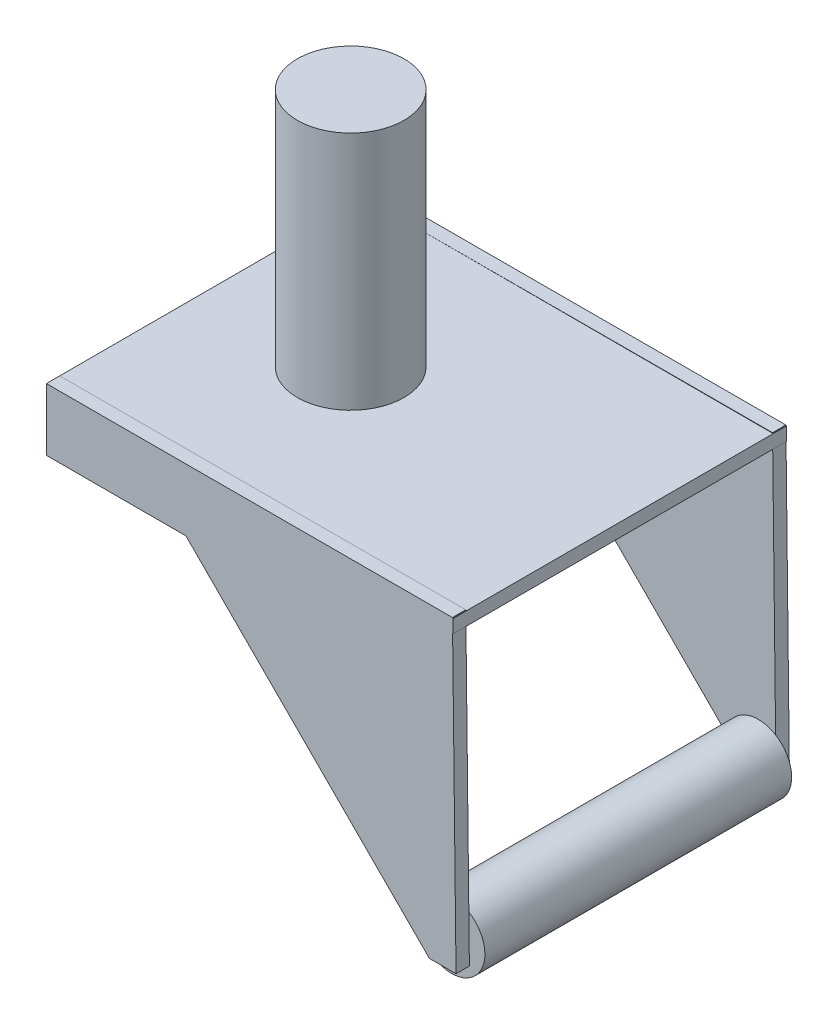
SolidWorks part; units mm, degrees
ref_plane "Plan de face" through (0, 0, 0) normal (0, 0, 1) x (1, 0, 0)
ref_plane "Plan de dessus" through (0, 0, 0) normal (0, 1, 0) x (1, 0, 0)
ref_plane "Plan de droite" through (0, 0, 0) normal (1, 0, 0) x (0, 0, -1)
sketch "Esquisse1" plane through (0, 0, 0) normal (0, 1, 0) x (1, 0, 0)
  line L1 (-15.25, 12.5) -> (15.25, 12.5)
  line L2 (-15.25, 12.5) -> (-15.25, -12.5)
  line L3 (-15.25, -12.5) -> (15.25, -12.5)
  line L4 (15.25, 12.5) -> (15.25, -12.5)
  line L5 (-15.25, 12.5) -> (15.25, -12.5) construction
  line L6 (-15.25, -12.5) -> (15.25, 12.5) construction
  point P0 (0, 0)
  dimension "D1" = 30.5
  dimension "D2" = 25
extrude "Boss.-Extru.1" add sketch "Esquisse1" along normal blind 1
ref_plane "Plan1" through (0, 0, 12.5) normal (0, 0, 1) x (1, 0, 0)
sketch "Esquisse2" plane through (0, 0, 12.5) normal (0, 0, 1) x (1, 0, 0)
  line L0 (15.1999, 1.0344) -> (15.4676, -21.9656)
  line L1 (15.4676, -21.9656) -> (13.4676, -21.9656)
  line L2 (13.4676, -21.9656) -> (-4.7854, -3.6591)
  line L3 (-4.7854, -3.6591) -> (-15.2331, -3.6591)
  line L4 (-15.2331, -3.6591) -> (-15.25, 1)
  line L5 (-15.25, 1) -> (-15.25, 0) construction
  line L6 (-15.25, 1) -> (15.1999, 1.0344)
  dimension "D1" = 2
  dimension "D2" = 23
extrude "Boss.-Extru.2" add sketch "Esquisse2" against normal blind 1
mirror "Symétrie1" about plane through (0, 0, 0) normal (0, 0, 1) of "Boss.-Extru.2"
sketch "Esquisse3" plane through (0, 0, -11.5) normal (0, 0, 1) x (1, 0, 0)
  circle A0 centre (14.1327, -20.6131) radius 2.5
  dimension "D1" = 5
extrude "Boss.-Extru.3" add sketch "Esquisse3" along normal blind 23
sketch "Esquisse4" plane through (0, 1, 0) normal (0, 1, 0) x (1, 0, 0)
  circle A0 centre (-4.9313, 0) radius 4
  dimension "D1" = 8
extrude "Boss.-Extru.4" add sketch "Esquisse4" along normal blind 18
cosmetic thread "Représentation de filetage1"
